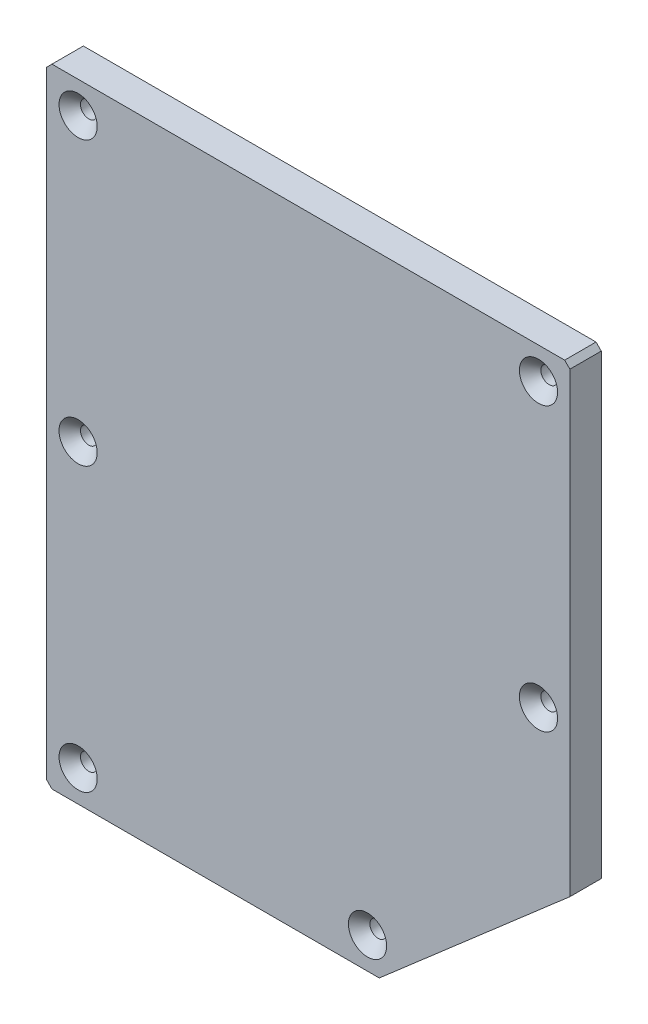
SolidWorks part; units mm, degrees
ref_plane "Front Plane" through (0, 0, 0) normal (0, 0, 1) x (1, 0, 0)
ref_plane "Top Plane" through (0, 0, 0) normal (0, 1, 0) x (1, 0, 0)
ref_plane "Right Plane" through (0, 0, 0) normal (1, 0, 0) x (0, 0, -1)
sketch "Sketch1" plane through (0, 0, 0) normal (0, 0, 1) x (1, 0, 0)
  line L778 (-40, 42.5997) -> (-40, -75.4003)
  line L779 (-40, 42.5997) -> (-40, -75.4003)
  line L780 (60, -44.7277) -> (60, 42.5997)
  line L781 (60, -44.7277) -> (60, 42.5997)
  line L880 (59, 43.5997) -> (-39, 43.5997)
  line L881 (59, 43.5997) -> (-39, 43.5997)
  line L884 (-39, -76.4003) -> (23.5648, -76.4003)
  line L885 (-39, -76.4003) -> (23.5648, -76.4003)
  line L886 (23.5648, -76.4003) -> (60, -44.7277)
  line L887 (23.5648, -76.4003) -> (60, -44.7277)
  line L1228 (60, 42.5997) -> (59, 43.5997)
  line L1229 (60, 42.5997) -> (59, 43.5997)
  line L1230 (-39, 43.5997) -> (-40, 42.5997)
  line L1231 (-39, 43.5997) -> (-40, 42.5997)
  line L1232 (-40, -75.4003) -> (-39, -76.4003)
  line L1233 (-40, -75.4003) -> (-39, -76.4003)
  dimension "D1" = 0
extrude "Boss-Extrude1" add sketch "Sketch1" along normal blind 6
hole_wizard "CSK for M3 Countersunk Flat Head Screw1" positions "3DSketch1" profile "Sketch4" countersink size "M3" standard "ISO" end condition up to next
sketch3d "3DSketch1"
  point P0 (-34, 37.5997, 6)
  point P2 (54, 37.5997, 6)
  point P4 (54, -16.4003, 6)
  point P22 (-34, -16.4003, 6)
  point P42 (-34, -70.4003, 6)
  point P44 (21.3215, -70.4003, 6)
sketch "Sketch4" plane through (-34, 37.5997, 6) normal (1, 0, 0) x (0, -1, 0)
  line L0 (0, 0) -> (0, 6)
  line L1 (0, 6) -> (1.6, 6)
  line L2 (1.6, 6) -> (1.6, 2.05)
  line L3 (1.6, 2.05) -> (3.65, 0)
  line L5 (3.65, 0) -> (0, 0)
  line L6 (-1.6, 2.05) -> (-3.65, 0) construction
  line L11 (0, -6.35) -> (0, 107.95) construction
  dimension "Thru Hole Dia." = 3.2
  dimension "Thru Hole Depth" = 6
  dimension "Near C'Sink Dia." = 7.3
  dimension "Near C'Sink Angle" = 90
